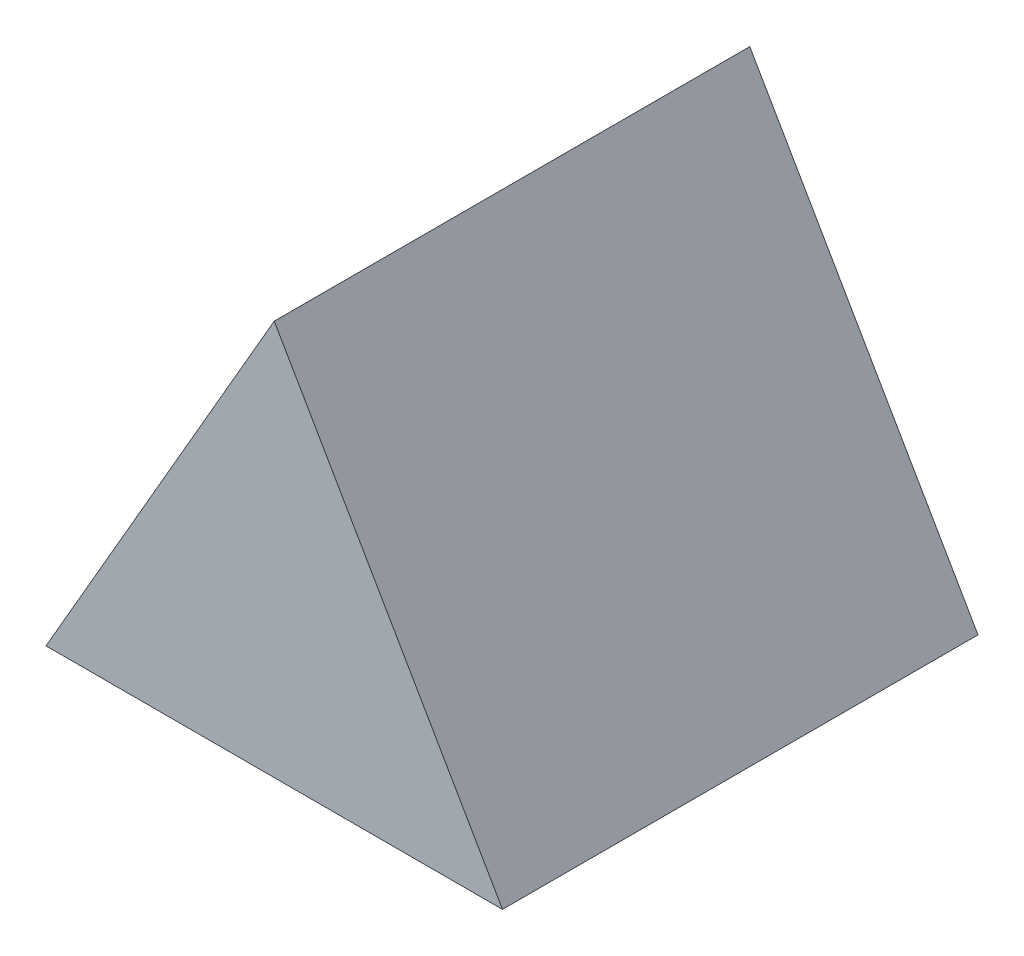
SolidWorks part; units mm, degrees
ref_plane "Alzado" through (0, 0, 0) normal (0, 0, 1) x (1, 0, 0)
ref_plane "Planta" through (0, 0, 0) normal (0, 1, 0) x (1, 0, 0)
ref_plane "Vista lateral" through (0, 0, 0) normal (1, 0, 0) x (0, 0, -1)
sketch "Croquis1" plane through (0, 0, 0) normal (0, 0, 1) x (1, 0, 0)
  line L0 (0.2045, 41.5692) -> (-23.7955, 0)
  line L1 (-23.7955, 0) -> (24.2045, 0)
  line L2 (24.2045, 0) -> (0.2045, 41.5692)
  dimension "D1" = 48
  dimension "D2" = 48
  dimension "D3" = 48
extrude "Saliente-Extruir2" add sketch "Croquis1" along normal blind 50
sketch "Croquis3" plane through (0, 0, 0) normal (0, 0, -1) x (-1, 0, 0)
  circle A0 centre (0, 14.2387) radius 2.4821
  point P0 (0, 14.2387)
  dimension "D1" = 4.9642
extrude "Cortar-Extruir1" cut sketch "Croquis3" against normal blind 10
